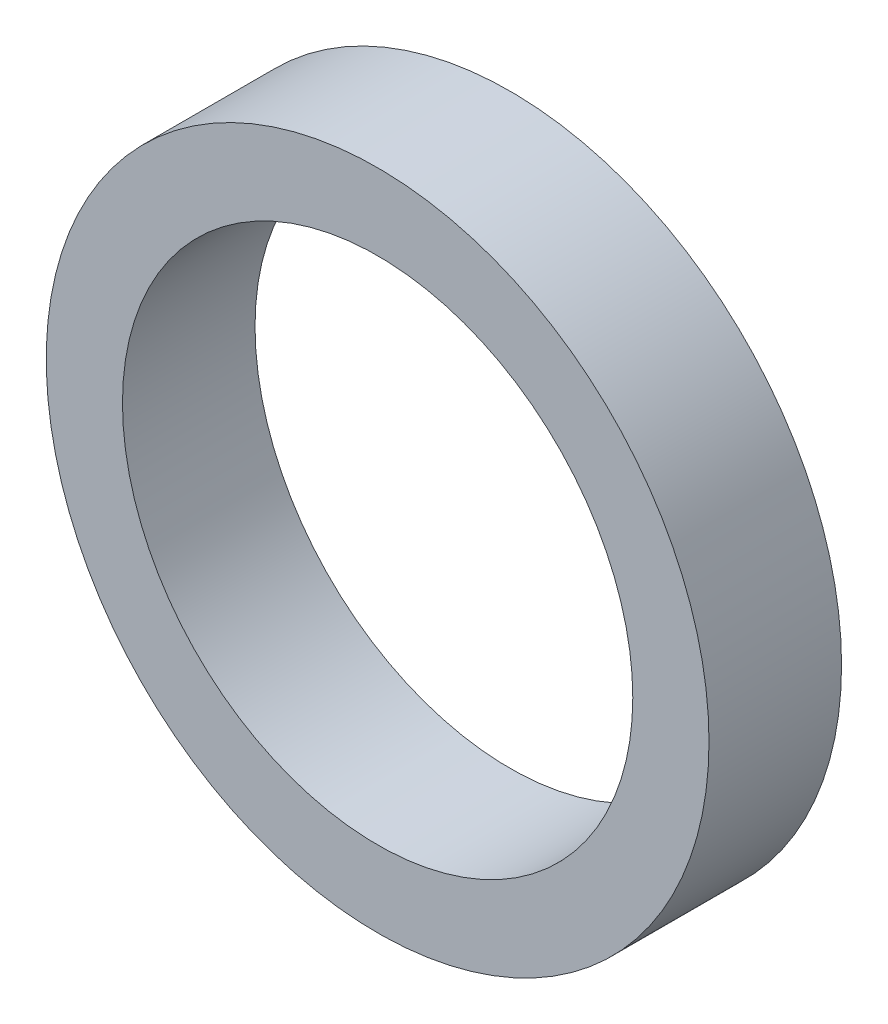
SolidWorks part; units mm, degrees
ref_plane "Płaszczyzna przednia" through (0, 0, 0) normal (0, 0, 1) x (1, 0, 0)
ref_plane "Płaszczyzna górna" through (0, 0, 0) normal (0, 1, 0) x (1, 0, 0)
ref_plane "Płaszczyzna prawa" through (0, 0, 0) normal (1, 0, 0) x (0, 0, -1)
sketch "Szkic1" plane through (0, 0, 0) normal (0, 0, 1) x (1, 0, 0)
  circle A0 centre (0, 0) radius 3.85
  circle A1 centre (0, 0) radius 5
  dimension "D1" = 7.7
  dimension "D2" = 10
extrude "Dodanie-wyciągnięcie1" add sketch "Szkic1" along normal blind 2 contours A1
